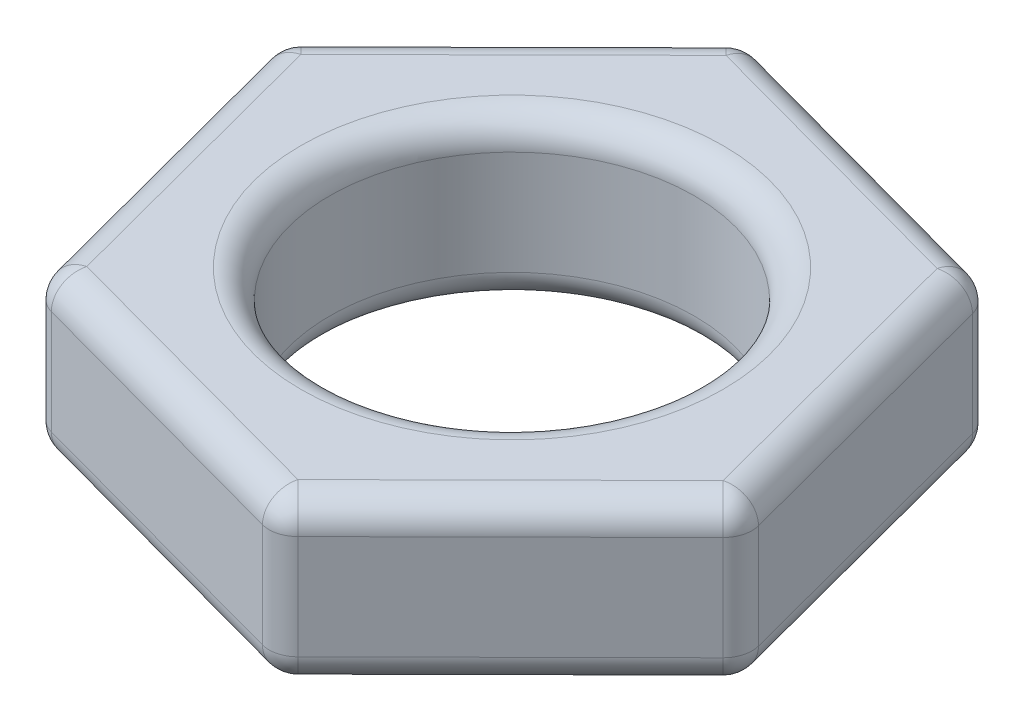
SolidWorks part; units mm, degrees
ref_plane "Front Plane" through (0, 0, 0) normal (0, 0, 1) x (1, 0, 0)
ref_plane "Top Plane" through (0, 0, 0) normal (0, 1, 0) x (1, 0, 0)
ref_plane "Right Plane" through (0, 0, 0) normal (1, 0, 0) x (0, 0, -1)
sketch "Sketch1" plane through (0, 0, 0) normal (0, 1, 0) x (1, 0, 0)
  line L1 (5.205, 5.1644) -> (-1.87, 7.0899)
  line L2 (-1.87, 7.0899) -> (-7.075, 1.9255)
  line L3 (-7.075, 1.9255) -> (-5.205, -5.1644)
  line L4 (-5.205, -5.1644) -> (1.87, -7.0899)
  line L5 (1.87, -7.0899) -> (7.075, -1.9255)
  line L6 (7.075, -1.9255) -> (5.205, 5.1644)
  circle A0 centre (0, 0) radius 6.35 construction
  circle A1 centre (0, 0) radius 4
  dimension "D1" = 8
  dimension "D2" = 12.7
extrude "Boss-Extrude1" add sketch "Sketch1" along normal blind 3.556
fillet "Fillet1" radius 0.635 2 edges at (0, 0, 4) (0, 3.556, 4)
fillet "Fillet2" radius 0.635 18 edges at (1.6675, 3.556, -6.1271) (1.6675, 0, -6.1271) (-6.14, 3.556, 1.6195) (-6.14, 0, 1.6195) (-1.87, 1.778, -7.0899) (-4.4725, 3.556, -4.5077) (-7.075, 1.778, -1.9255) (-4.4725, 0, -4.5077) (-5.205, 1.778, 5.1644) (-1.6675, 3.556, 6.1271) (-1.6675, 0, 6.1271) (6.14, 3.556, -1.6195) (5.205, 1.778, -5.1644) (6.14, 0, -1.6195) (1.87, 1.778, 7.0899) (4.4725, 3.556, 4.5077) (7.075, 1.778, 1.9255) (4.4725, 0, 4.5077)
